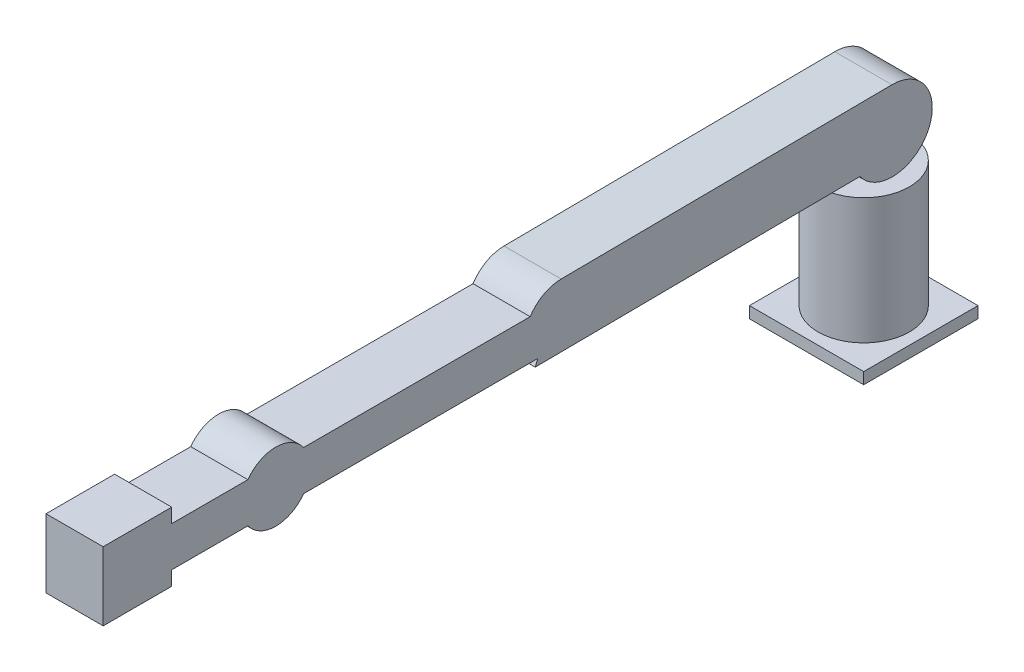
SolidWorks part; units mm, degrees
ref_plane "Front Plane" through (0, 0, 0) normal (0, 0, 1) x (1, 0, 0)
ref_plane "Top Plane" through (0, 0, 0) normal (0, 1, 0) x (1, 0, 0)
ref_plane "Right Plane" through (0, 0, 0) normal (1, 0, 0) x (0, 0, -1)
sketch "Sketch1" plane through (0, 0, 0) normal (0, 1, 0) x (1, 0, 0)
  circle A0 centre (0, 0) radius 40
  dimension "D1" = 80
extrude "Boss-Extrude1" add sketch "Sketch1" along normal blind 110
sketch "Sketch2" plane through (0, 0, 0) normal (0, -1, 0) x (1, 0, 0)
  line L1 (-50, 50) -> (50, 50)
  line L2 (-50, 50) -> (-50, -50)
  line L3 (-50, -50) -> (50, -50)
  line L4 (50, 50) -> (50, -50)
  line L5 (-50, 50) -> (50, -50) construction
  line L6 (-50, -50) -> (50, 50) construction
  point P0 (0, 0)
  dimension "D1" = 100
extrude "Boss-Extrude2" add sketch "Sketch2" along normal blind 10
sketch "Sketch3" plane through (0, 0, 0) normal (1, 0, 0) x (0, 0, -1)
  line L0 (0, 145) -> (-289.3966, 145) construction
  line L1 (40, 110) -> (-40, 110) construction
  line L2 (-289.3966, 145) -> (-539.3966, 145) construction
  line L3 (-539.3966, 145) -> (-630.3966, 145) construction
  line L4 (-289.6773, 177.4988) -> (-0.3024, 179.9987)
  line L21 (-0.3024, 179.9987) -> (-28.3484, 124.4728)
  line L22 (-28.3484, 124.4728) -> (-312.3776, 122.019)
  line L23 (-289.6773, 177.4988) -> (-312.3776, 122.019)
  line L28 (-539.3966, 127.5) -> (-630.3966, 127.5)
  line L29 (-630.3966, 127.5) -> (-630.3966, 162.5)
  line L30 (-630.3966, 162.5) -> (-539.3966, 162.5)
  line L33 (-539.3966, 162.5) -> (-539.3966, 127.5)
  line L36 (-539.3966, 162.5) -> (-289.3966, 162.5)
  line L37 (-289.3966, 162.5) -> (-289.3966, 127.5)
  line L38 (-289.3966, 127.5) -> (-539.3966, 127.5)
  line L39 (-539.3966, 127.5) -> (-539.3966, 162.5)
  line L40 (-630.3966, 175) -> (-630.3966, 115)
  line L45 (-630.3966, 115) -> (-690.3966, 115)
  line L46 (-690.3966, 115) -> (-690.3966, 175)
  line L47 (-690.3966, 175) -> (-630.3966, 175)
  circle A0 centre (-289.3966, 145) radius 32.5
  circle A1 centre (0, 145) radius 35
  circle A2 centre (-539.3966, 145) radius 30
  point P11 (-539.3966, 145)
  point P14 (-630.3966, 145)
  point P22 (-539.3966, 145)
  point P25 (-289.3966, 145)
  point P27 (-630.3966, 145)
  dimension "D5" = 250
  dimension "D6" = 65
  dimension "D7" = 91
  dimension "D3" = 70
  dimension "D14" = 60
  dimension "D2" = 0
  dimension "D4" = 55.2816
  dimension "D8" = 35
  dimension "D9" = 35
  dimension "D10" = 180
  dimension "D11" = 180
  dimension "D12" = 60
  dimension "D13" = 60
  dimension "D18" = 289.3966
extrude "Boss-Extrude3" add sketch "Sketch3" along normal mid plane 50 separate body
